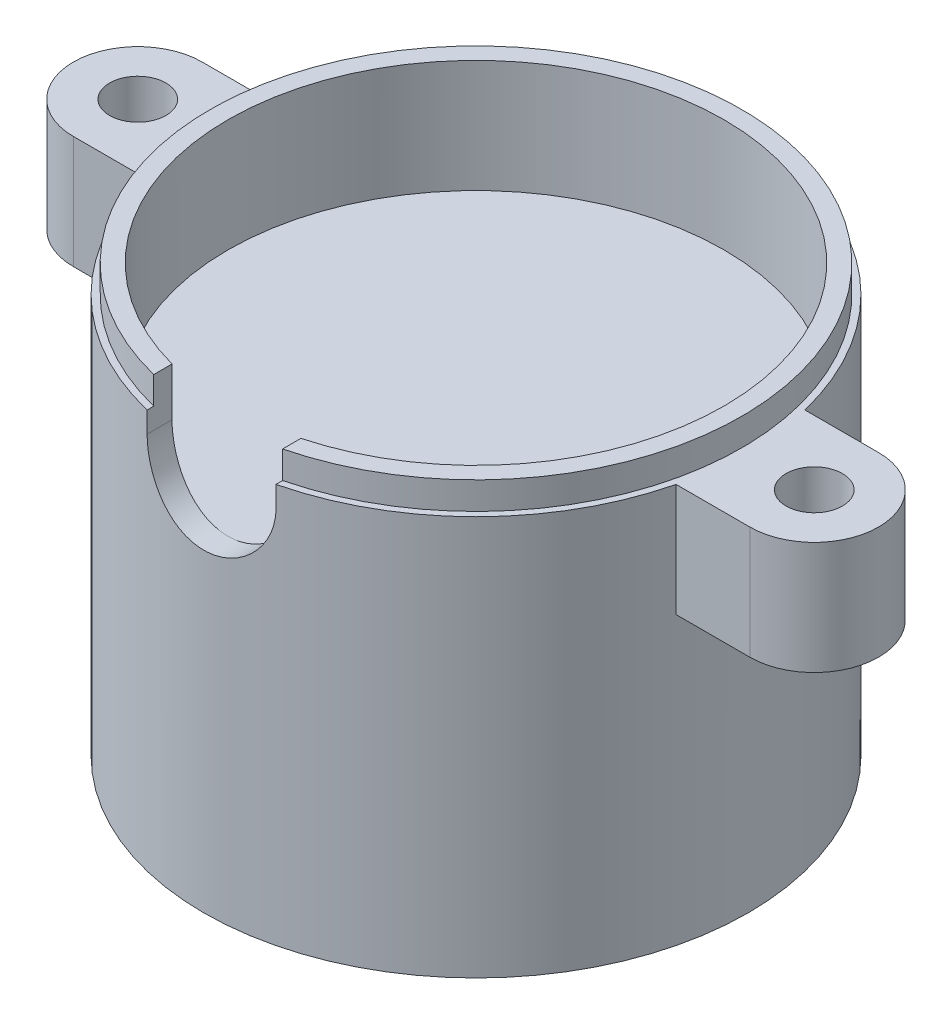
SolidWorks part; units mm, degrees
ref_plane "Front Plane" through (0, 0, 0) normal (0, 0, 1) x (1, 0, 0)
ref_plane "Top Plane" through (0, 0, 0) normal (0, 1, 0) x (1, 0, 0)
ref_plane "Right Plane" through (0, 0, 0) normal (1, 0, 0) x (0, 0, -1)
sketch "Sketch1" plane through (0, 0, 0) normal (0, 0, 1) x (1, 0, 0)
  line L0 (0, 0) -> (0, 24291.6947) construction
  line L1 (0, 12) -> (15.4, 12)
  line L2 (15.4, 12) -> (15.4, 0)
  line L3 (15.4, 0) -> (16.9, 0)
  line L4 (16.9, 0) -> (16.9, 24.8)
  line L5 (16.5, 26.5) -> (15.4, 26.5)
  line L6 (15.4, 26.5) -> (15.4, 19.5)
  line L7 (15.4, 19.5) -> (0, 19.5)
  line L8 (0, 19.5) -> (0, 12)
  line L9 (16.5, 26.5) -> (16.5, 24.8)
  line L10 (16.5, 24.8) -> (16.9, 24.8)
  point P12 (16.15, 0)
  dimension "D1" = 30.8
  dimension "D2" = 7
  dimension "D3" = 30.8
  dimension "D4" = 1.5
  dimension "D5" = 12
  dimension "D6" = 26.5
  dimension "D7" = 33
  dimension "D8" = 1.7
revolve "Revolve1" add sketch "Sketch1" angle 360 about L0
ref_plane "Plane1" through (0, 0, 16.9) normal (0, 0, 1) x (1, 0, 0)
sketch "Sketch3" plane through (0, 0, 16.9) normal (0, 0, 1) x (1, 0, 0)
  line L0 (-4, 26.5) -> (-4, 23.5)
  line L1 (16.9, 26.5) -> (-16.9, 26.5) construction
  line L2 (4, 23.5) -> (4, 26.5)
  line L3 (15.4, 26.5) -> (-15.4, 26.5) construction
  line L4 (4, 26.5) -> (-4, 26.5)
  line L5 (0, 26.5) -> (0, 19.5) construction
  arc A0 (-4, 23.5) -> (4, 23.5) centre (0, 23.5) ccw
  dimension "D1" = 8
  dimension "D2" = 7
extrude "Cut-Extrude1" cut sketch "Sketch3" against normal blind 10
sketch "Sketch4" plane through (0, 24.8, 0) normal (0, 1, 0) x (1, 0, 0)
  line L0 (21, -4) -> (16.4198, -4)
  line L1 (21, 4) -> (16.4198, 4)
  circle A0 centre (21, 0) radius 1.75
  arc A1 (21, -4) -> (21, 4) centre (21, 0) ccw
  arc A2 (4, -16.4198) -> (-4, -16.4198) centre (0, 0) ccw construction
  arc A3 (16.4198, 4) -> (16.4198, -4) centre (0, 0) cw
  dimension "D2" = 3.5
  dimension "D3" = 4
  dimension "D1" = 21
extrude "Boss-Extrude1" add sketch "Sketch4" against normal blind 7
sketch "Sketch5" plane through (0, 17.8, 0) normal (0, -1, 0) x (1, 0, 0)
  line L1 (18.35, -1.53) -> (21, -3.06)
  line L2 (21, -3.06) -> (23.65, -1.53)
  line L3 (23.65, -1.53) -> (23.65, 1.53)
  line L4 (23.65, 1.53) -> (21, 3.06)
  line L5 (21, 3.06) -> (18.35, 1.53)
  line L6 (18.35, 1.53) -> (18.35, -1.53)
  circle A0 centre (21, 0) radius 2.65 construction
  dimension "D1" = 5.3
extrude "Cut-Extrude2" cut sketch "Sketch5" against normal blind 3
mirror "Mirror1" about plane through (0, 0, 0) normal (1, 0, 0) of "Cut-Extrude2", "Boss-Extrude1"
